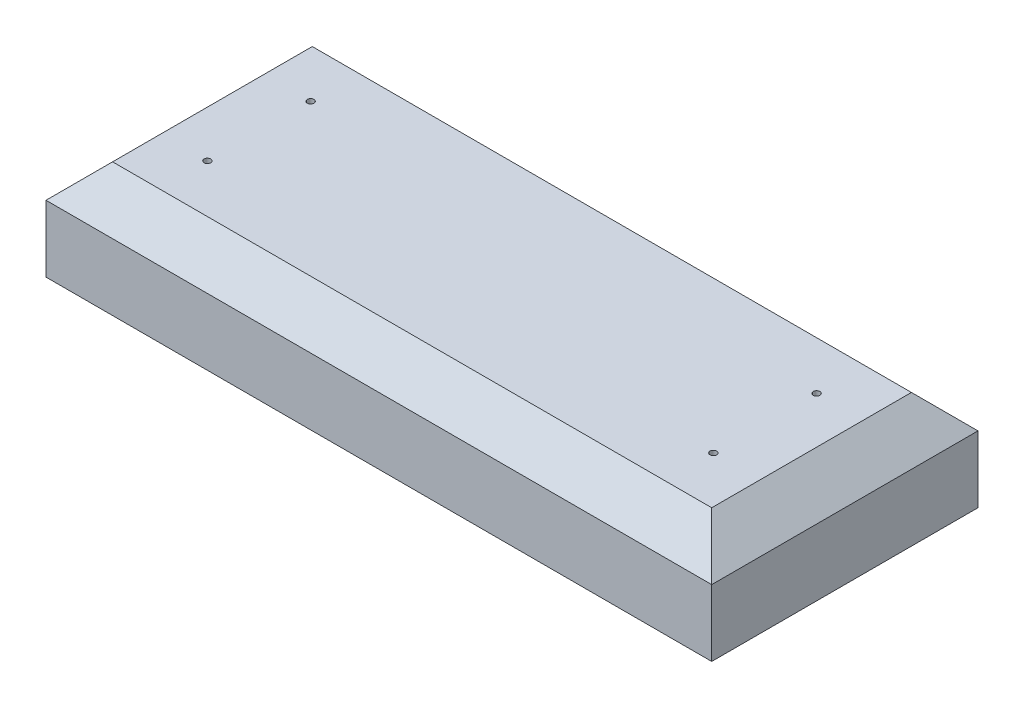
SolidWorks part; units mm, degrees
ref_plane "Front Plane" through (0, 0, 0) normal (0, 0, 1) x (1, 0, 0)
ref_plane "Top Plane" through (0, 0, 0) normal (0, 1, 0) x (1, 0, 0)
ref_plane "Right Plane" through (0, 0, 0) normal (1, 0, 0) x (0, 0, -1)
sketch "Sketch1" plane through (0, 0, 0) normal (0, 1, 0) x (1, 0, 0)
  line L1 (-174.5501, 67.7892) -> (25.4499, 67.7892)
  line L2 (-174.5501, 67.7892) -> (-174.5501, -12.2108)
  line L3 (-174.5501, -12.2108) -> (25.4499, -12.2108)
  line L4 (25.4499, 67.7892) -> (25.4499, -12.2108)
  line L5 (-174.5501, 67.7892) -> (25.4499, -12.2108) construction
  line L6 (-174.5501, -12.2108) -> (25.4499, 67.7892) construction
  point P0 (-74.5501, 27.7892)
  dimension "D1" = 200
  dimension "D2" = 80
extrude "Boss-Extrude1" add sketch "Sketch1" along normal blind 30
chamfer "Chamfer1" distance 10 angle 45 4 edges at (-174.5501, 30, -27.7892) (-74.5501, 30, -67.7892) (25.4499, 30, -27.7892) (-74.5501, 30, 12.2108)
sketch "Sketch2" plane through (0, 30, 0) normal (0, 1, 0) x (1, 0, 0)
  circle A0 centre (1.4499, 43.2892) radius 1
extrude "Cut-Extrude1" cut sketch "Sketch2" against normal blind 40
pattern_linear "LPattern1" count 3 spacing 152 along (-1, 0, 0) count 2 spacing 31 along (0, 0, 1) of "Cut-Extrude1"
